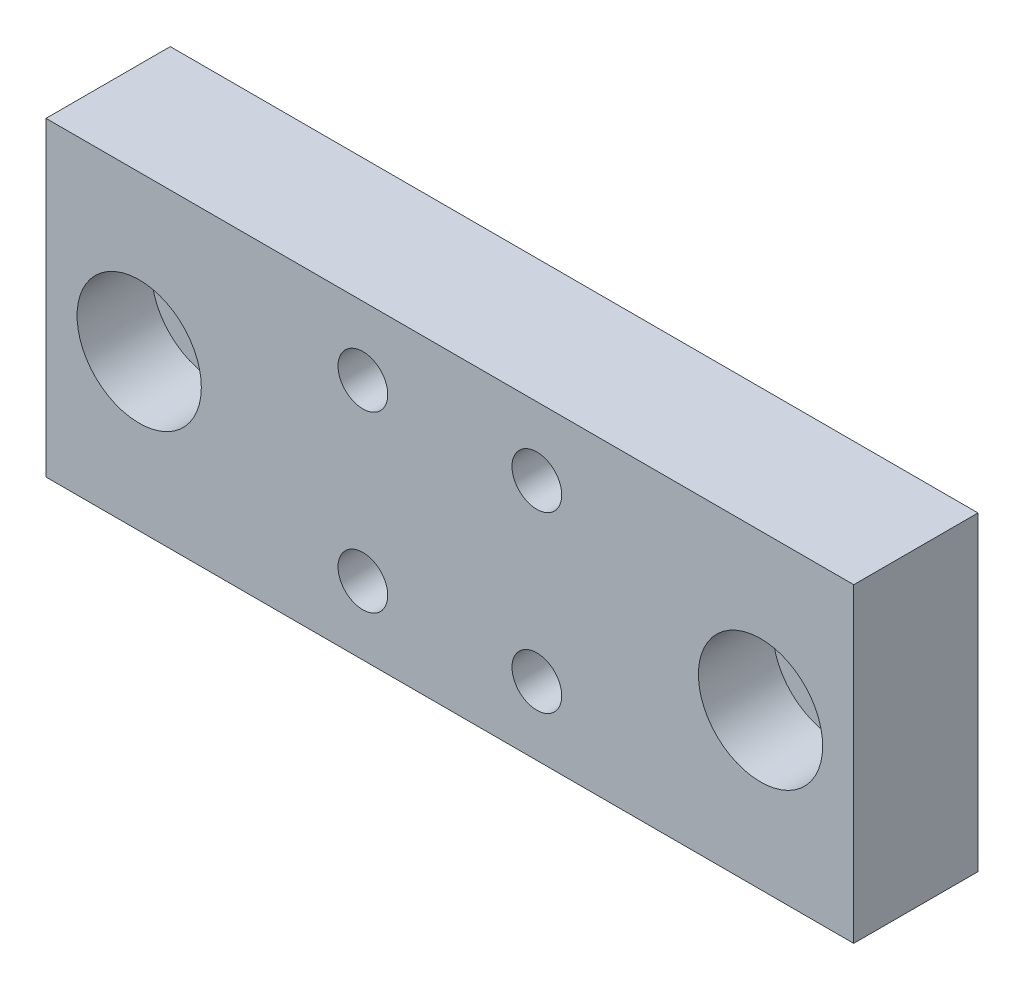
SolidWorks part; units mm, degrees
ref_plane "Front Plane" through (0, 0, 0) normal (0, 0, 1) x (1, 0, 0)
ref_plane "Top Plane" through (0, 0, 0) normal (0, 1, 0) x (1, 0, 0)
ref_plane "Right Plane" through (0, 0, 0) normal (1, 0, 0) x (0, 0, -1)
sketch "Sketch1" plane through (0, 0, 0) normal (0, 0, 1) x (1, 0, 0)
  line L0 (-57.8051, 0) -> (58.8205, 0) construction
  line L1 (-47.5214, -12.5) -> (17.4786, -12.5)
  line L2 (-47.5214, -12.5) -> (-47.5214, 12.5)
  line L3 (-47.5214, 12.5) -> (17.4786, 12.5)
  line L4 (17.4786, -12.5) -> (17.4786, 12.5)
  point P0 (0, 0)
  point P8 (-47.5214, 0)
  point P9 (0, 0)
  dimension "D1" = 25
extrude "Boss-Extrude1" add sketch "Sketch1" along normal blind 10
sketch "Sketch3" plane through (0, 0, 0) normal (0, 0, -1) x (-1, 0, 0)
  line L0 (15.0214, -12.5) -> (15.0214, 12.5) construction
  line L1 (47.5214, -12.5) -> (-17.4786, -12.5) construction
  line L2 (47.5214, 12.5) -> (-17.4786, 12.5) construction
  line L4 (28.0214, 12.5) -> (2.0214, 12.5) construction
  line L5 (28.0214, 12.5) -> (28.0214, -12.5) construction
  line L6 (28.0214, -12.5) -> (2.0214, -12.5) construction
  line L7 (2.0214, 12.5) -> (2.0214, -12.5) construction
  line L10 (22.0214, 7) -> (8.0214, 7) construction
  line L11 (22.0214, 7) -> (22.0214, -7) construction
  line L12 (22.0214, -7) -> (8.0214, -7) construction
  line L13 (8.0214, 7) -> (8.0214, -7) construction
  line L14 (22.0214, 7) -> (8.0214, -7) construction
  line L15 (22.0214, -7) -> (8.0214, 7) construction
  circle A0 centre (22.0214, -7) radius 2
  circle A1 centre (8.0214, -7) radius 2
  circle A2 centre (8.0214, 7) radius 2
  circle A3 centre (22.0214, 7) radius 2
  point P2 (15.0214, 0)
  point P9 (15.0214, 0)
  dimension "D2" = 4
  dimension "D3" = 4
  dimension "D4" = 4
  dimension "D5" = 4
  dimension "D1" = 26
  dimension "D6" = 14
  dimension "D7" = 14
extrude "Cut-Extrude1" cut sketch "Sketch3" against normal blind 10
sketch "Sketch5" plane through (0, 0, 0) normal (0, 0, -1) x (-1, 0, 0)
  circle A0 centre (22.0214, -7) radius 4.1
  circle A1 centre (8.0214, -7) radius 4.1
  circle A2 centre (8.0214, 7) radius 4.1
  circle A3 centre (22.0214, 7) radius 4.1
  dimension "D1" = 8.2
  dimension "D2" = 8.2
  dimension "D3" = 8.2
  dimension "D4" = 8.2
extrude "Cut-Extrude2" cut sketch "Sketch5" against normal blind 3.7
sketch "Sketch8" plane through (0, 0, 0) normal (0, 0, -1) x (-1, 0, 0)
  line L0 (57.8051, 0) -> (-58.8205, 0) construction
  line L1 (47.5214, -12.5) -> (47.5214, 12.5) construction
  line L2 (-17.4786, -12.5) -> (-17.4786, 12.5) construction
  point P0 (40.0214, 0)
  point P1 (-9.9786, 0)
  dimension "D1" = 7.5
  dimension "D2" = 7.5
sketch "Sketch9" plane through (0, 0, 10) normal (0, 0, 1) x (1, 0, 0)
  point P0 (9.9786, 0)
  point P2 (-40.0214, 0)
sketch "Sketch12" plane through (0, 0, 10) normal (0, 0, 1) x (1, 0, 0)
  circle A0 centre (-40.0214, 0) radius 3
  circle A1 centre (9.9786, 0) radius 3
  dimension "D1" = 6
  dimension "D2" = 6
extrude "Cut-Extrude3" cut sketch "Sketch12" against normal blind 24.2
sketch "Sketch13" plane through (0, 0, 10) normal (0, 0, 1) x (1, 0, 0)
  circle A0 centre (-40.0214, 0) radius 5
  circle A1 centre (9.9786, 0) radius 5
  dimension "D1" = 10
  dimension "D2" = 10
extrude "Cut-Extrude4" cut sketch "Sketch13" against normal blind 6
equation "\"3.75mmmm\"=3.7"
